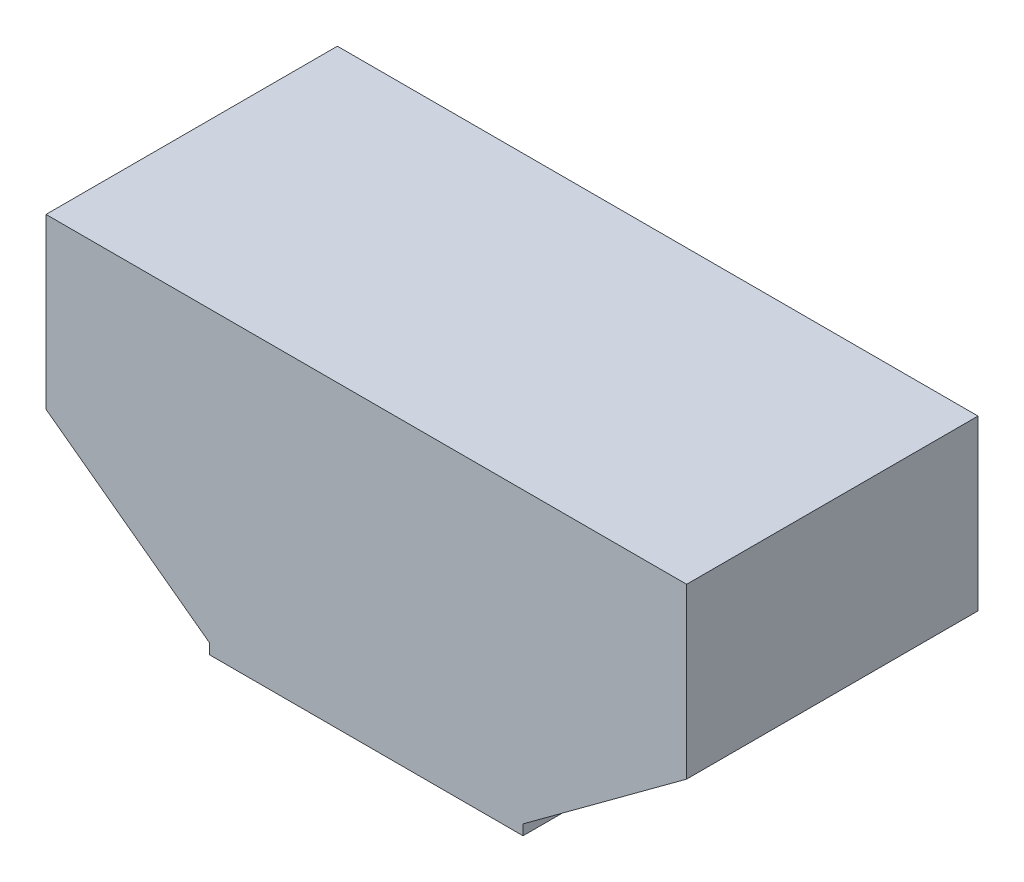
SolidWorks part; units mm, degrees
ref_plane "Front Plane" through (0, 0, 0) normal (0, 0, 1) x (1, 0, 0)
ref_plane "Top Plane" through (0, 0, 0) normal (0, 1, 0) x (1, 0, 0)
ref_plane "Right Plane" through (0, 0, 0) normal (1, 0, 0) x (0, 0, -1)
sketch "Sketch1" plane through (0, 0, 0) normal (0, 0, 1) x (1, 0, 0)
  line L0 (-2063.2072, -609.6) -> (2063.2072, -609.6) construction
  line L1 (-2087.4164, -520.7) -> (2087.4164, -520.7) construction
  line L2 (0, 0) -> (0, -520.7) construction
  line L3 (-577.85, -2072.3236) -> (577.85, -2072.3236)
  line L6 (577.85, -2072.3236) -> (577.85, -2034.2236)
  line L7 (577.85, -2034.2236) -> (-577.85, -2034.2236) construction
  line L8 (-577.85, -2034.2236) -> (-577.85, -2072.3236)
  line L9 (-577.85, -2034.2236) -> (-1181.1, -1589.7236)
  line L10 (-1181.1, -1589.7236) -> (-1181.1, -967.4236)
  line L11 (-1181.1, -967.4236) -> (1181.1, -967.4236)
  line L12 (1181.1, -967.4236) -> (1181.1, -1589.7236)
  line L13 (1181.1, -1589.7236) -> (577.85, -2034.2236)
  circle A0 centre (0, 0) radius 2240.28 construction
  circle A1 centre (0, 0) radius 2151.38 construction
  circle A4 centre (0, -520.7) radius 274.5589 construction
  point P6 (0, -2151.38)
  point P21 (0, -2034.2236)
  dimension "D1" = 4480.56
  dimension "D2" = 88.9
  dimension "D5" = 1155.7
  dimension "D7" = 622.3
  dimension "D3" = 1541.78
  dimension "D4" = 88.9
  dimension "D6" = 1066.8
  dimension "D8" = 38.1
  dimension "D9" = 2362.2
extrude "Boss-Extrude1" add sketch "Sketch1" along normal blind 1074.42
